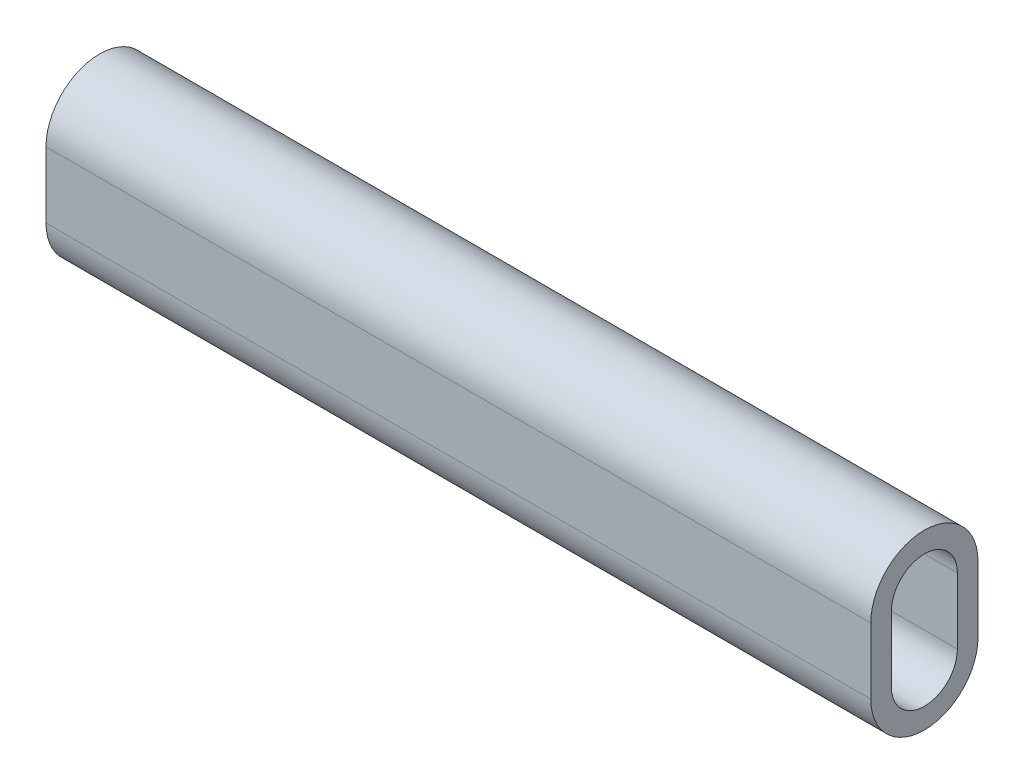
SolidWorks part; units mm, degrees
ref_plane "Front Plane" through (0, 0, 0) normal (0, 0, 1) x (1, 0, 0)
ref_plane "Top Plane" through (0, 0, 0) normal (0, 1, 0) x (1, 0, 0)
ref_plane "Right Plane" through (0, 0, 0) normal (1, 0, 0) x (0, 0, -1)
sketch "Sketch1" plane through (0, 0, 0) normal (1, 0, 0) x (0, 0, -1)
  line L0 (0, -0.8) -> (0, 0.8) construction
  line L1 (-0.8, -0.8) -> (-0.8, 0.8)
  line L2 (0.8, -0.8) -> (0.8, 0.8)
  line L3 (-1.3, -0.8) -> (-1.3, 0.8)
  line L4 (1.3, -0.8) -> (1.3, 0.8)
  arc A0 (-0.8, -0.8) -> (0.8, -0.8) centre (0, -0.8) ccw
  arc A1 (0.8, 0.8) -> (-0.8, 0.8) centre (0, 0.8) ccw
  arc A2 (1.3, 0.8) -> (-1.3, 0.8) centre (0, 0.8) ccw
  arc A3 (-1.3, -0.8) -> (1.3, -0.8) centre (0, -0.8) ccw
  point P2 (0, 0)
  dimension "D1" = 0.8
  dimension "D2" = 1.6
  dimension "D3" = 0.5
extrude "Boss-Extrude1" add sketch "Sketch1" along normal blind 20
